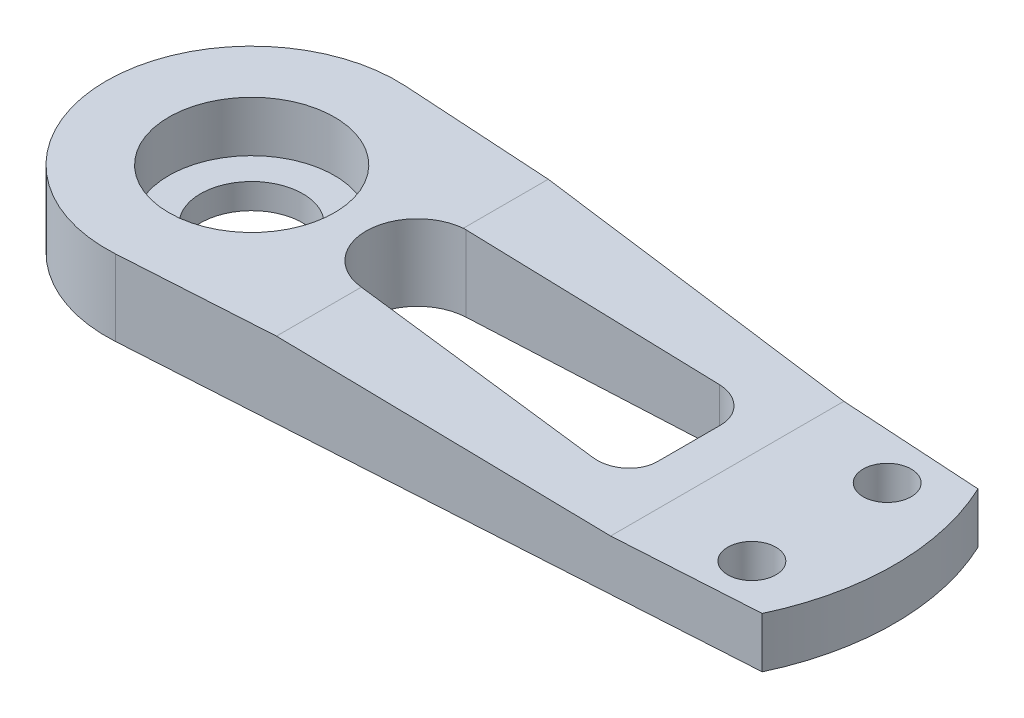
SolidWorks part; units mm, degrees
ref_plane "Front Plane" through (0, 0, 0) normal (0, 0, 1) x (1, 0, 0)
ref_plane "Top Plane" through (0, 0, 0) normal (0, 1, 0) x (1, 0, 0)
ref_plane "Right Plane" through (0, 0, 0) normal (1, 0, 0) x (0, 0, -1)
sketch "Sketch1" plane through (0, 0, 0) normal (0, 1, 0) x (1, 0, 0)
  line L16 (0.7021, 11.4786) -> (48.9, 8.5306)
  line L19 (0.7021, -11.4786) -> (48.9, -8.5306)
  line L36 (48.9, 8.5306) -> (48.9, -8.5306) construction
  line L37 (0, 0) -> (69.5, 0) construction
  line L38 (44.9, 5.35) -> (44.9, -5.35) construction
  line L46 (12.8982, 4.045) -> (31.9754, 4.9969)
  line L47 (34.6, 2.5) -> (34.6, -2.5)
  line L48 (31.9754, -4.9969) -> (12.8982, -4.045)
  line L49 (3.3946, 18.3385) -> (70.5921, 5.8998) construction
  line L50 (0, -18.65) -> (70.5664, -5.9045) construction
  arc A1 (0.7021, 11.4786) -> (0.7021, -11.4786) centre (0, 0) ccw
  circle A2 centre (44.9, -5.35) radius 1.9
  circle A5 centre (0, 0) radius 4.05
  circle A6 centre (44.9, 5.35) radius 1.9
  arc A7 (34.6, 2.5) -> (31.9754, 4.9969) centre (32.1, 2.5) ccw
  arc A8 (31.9754, -4.9969) -> (34.6, -2.5) centre (32.1, -2.5) ccw
  arc A9 (12.8982, 4.045) -> (12.8982, -4.045) centre (13.1, 0) ccw
  circle A10 centre (0, 0) radius 18.65 construction
  circle A12 centre (69.5, 0) radius 6 construction
  arc A13 (48.9, -8.5306) -> (48.9, 8.5306) centre (30.8105, 0) ccw
  point P8 (34.75, 0)
  point P10 (44.9, 0)
  point P11 (48.9, 0)
  point P13 (34.6, 0)
  dimension "D1" = 23
  dimension "D2" = 44.9
  dimension "D3" = 3.8
  dimension "D4" = 8.1
  dimension "D6" = 37.3
  dimension "D7" = 12
  dimension "D14" = 2.5
  dimension "D15" = 20
  dimension "D5" = 93.5
  dimension "D8" = 69.5
  dimension "D9" = 10.7
  dimension "D10" = 4
  dimension "D11" = 5
  dimension "D12" = 13.1
  dimension "D13" = 19
  dimension "D16" = 24.6
extrude "Boss-Extrude2" add sketch "Sketch1" along normal blind 6
sketch "Sketch2" plane through (0, 6, 0) normal (0, 1, 0) x (1, 0, 0)
  circle A0 centre (0, 0) radius 6.55
  dimension "D1" = 13.1
extrude "Cut-Extrude3" cut sketch "Sketch2" against normal blind 4
sketch "Sketch3" plane through (0, 0, 0) normal (0, 0, 1) x (1, 0, 0)
  line L0 (50.8105, 4) -> (37.6034, 4)
  line L2 (37.6034, 4) -> (12.708, 6)
  line L4 (12.708, 6) -> (50.8105, 6)
  line L5 (50.8105, 6) -> (50.8105, 4)
  line L6 (0.7021, 6) -> (48.9, 6) construction
  line L8 (50.8105, 0) -> (50.8105, 6) construction
  dimension "D1" = 2
extrude "Cut-Extrude2" cut sketch "Sketch3" against normal blind 16 and the other way blind 21
